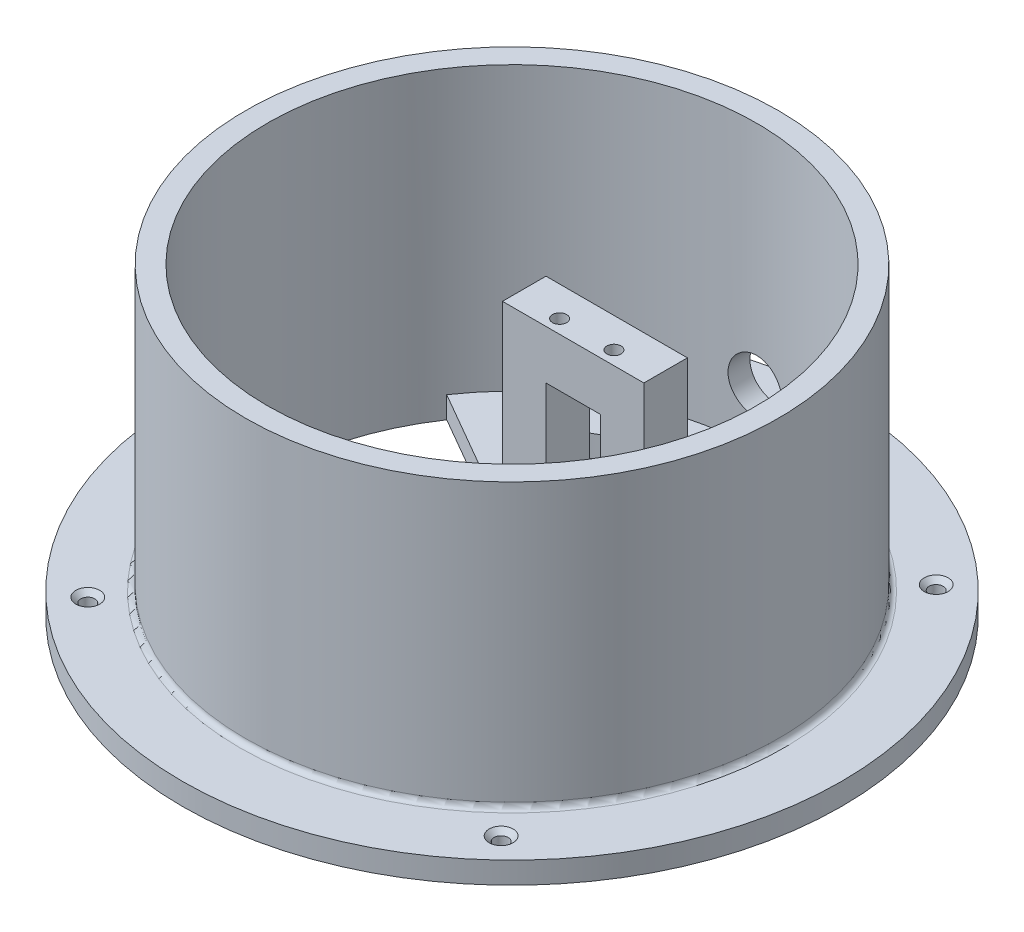
SolidWorks part; units mm, degrees
ref_plane "Front Plane" through (0, 0, 0) normal (0, 0, 1) x (1, 0, 0)
ref_plane "Top Plane" through (0, 0, 0) normal (0, 1, 0) x (1, 0, 0)
ref_plane "Right Plane" through (0, 0, 0) normal (1, 0, 0) x (0, 0, -1)
sketch "Sketch3" plane through (0, 0, 0) normal (0, 1, 0) x (1, 0, 0)
  circle A0 centre (0, 0) radius 60.625
  circle A1 centre (0, 0) radius 45
  dimension "D1" = 121.25
  dimension "D2" = 90
extrude "Boss-Extrude1" add sketch "Sketch3" along normal blind 4
sketch "Sketch5" plane through (0, 4, 0) normal (0, 1, 0) x (1, 0, 0)
  circle A0 centre (0, 0) radius 45 construction
  circle A1 centre (0, 0) radius 45
  circle A2 centre (0, 0) radius 49
  dimension "D1" = 4
extrude "Boss-Extrude2" add sketch "Sketch5" along normal blind 52
sketch "Sketch6" plane through (0, 0, 0) normal (1, 0, 0) x (0, 0, -1)
  line L0 (-46.75, 38) -> (-31.75, 38)
  line L1 (-31.75, 38) -> (-31.75, 30)
  line L3 (-46.75, 30) -> (-46.75, 38)
  line L4 (-45, 57.2969) -> (-45, 0)
  line L5 (-60.625, 0) -> (60.625, 0) construction
  line L6 (-31.75, 30) -> (-45, 16.75)
  line L7 (-45, 0) -> (45, 0) construction
  line L8 (11.25, 38) -> (19.25, 38)
  line L9 (11.25, 38) -> (11.25, 0)
  line L10 (11.25, 0) -> (19.25, 0)
  line L11 (19.25, 38) -> (19.25, 0)
  line L12 (49, 56) -> (-49, 56) construction
  line L13 (45, 56) -> (-45, 56) construction
  line L14 (-45, 16.75) -> (-46.75, 15)
  line L15 (-46.75, 30) -> (-46.75, 15)
  point P18 (-31.75, 34)
  dimension "D1" = 8
  dimension "D2" = 18
  dimension "D3" = 11.25
  dimension "D4" = 43
  dimension "D5" = 15
  dimension "D6" = 8
  dimension "D7" = 45
  dimension "D8" = 18
extrude "Boss-Extrude3" add sketch "Sketch6" along normal mid plane 26 contours L6 L14 L15 L3 L0 L1 | L9 L8 L11 L10
sketch "Sketch7" plane through (0, 0, -11.25) normal (0, 0, 1) x (1, 0, 0)
  line L0 (13, 38) -> (-13, 38) construction
  line L1 (-5, 5) -> (5, 5)
  line L2 (-5, 5) -> (-5, 29)
  line L3 (-5, 29) -> (5, 29)
  line L4 (5, 5) -> (5, 29)
  line L5 (-5, 5) -> (5, 29) construction
  line L6 (-5, 29) -> (5, 5) construction
  line L7 (13, 0) -> (-13, 0) construction
  point P0 (0, 17)
  dimension "D1" = 9
  dimension "D2" = 10
  dimension "D3" = 5
extrude "Cut-Extrude1" cut sketch "Sketch7" against normal blind 26
sketch "Sketch8" plane through (0, 0, -11.25) normal (0, 0, 1) x (1, 0, 0)
  circle A0 centre (0, 14) radius 5
  dimension "D1" = 10
  dimension "D2" = 14
extrude "Cut-Extrude2" cut sketch "Sketch8" against normal blind 55
sketch "Sketch9" plane through (0, 38, 0) normal (0, 1, 0) x (1, 0, 0)
  line L0 (5, 13.75) -> (-5, 13.75) construction
  line L1 (5, -34.25) -> (-5, -34.25) construction
  line L2 (13, -31.75) -> (-13, -31.75) construction
  circle A0 centre (-5, 13.75) radius 1.3
  circle A1 centre (5, 13.75) radius 1.3
  circle A2 centre (5, -34.25) radius 1.3
  circle A3 centre (-5, -34.25) radius 1.3
  dimension "D1" = 2.6
  dimension "D2" = 5
  dimension "D3" = 10
  dimension "D4" = 10
  dimension "D5" = 2.5
  dimension "D6" = 48
extrude "Cut-Extrude5" cut sketch "Sketch9" against normal blind 7.2 contours A1 | A2 | A3 | A0
sketch "Sketch10" plane through (0, 0, 0) normal (0, -1, 0) x (1, 0, 0)
  line L0 (13, -11.25) -> (-13, -11.25) construction
  line L1 (13, -11.25) -> (-13, -11.25)
  line L2 (0, 10.5988) -> (0, -40.7132) construction
  line L3 (-13, -11.25) -> (-37.2484, -25.2498)
  line L4 (13, -11.25) -> (37.2484, -25.2498)
  line L5 (19.5167, -24.25) -> (24.9065, -27.3618)
  line L7 (-19.5167, -24.25) -> (-24.9065, -27.3618)
  line L8 (-19.5167, -24.25) -> (19.5167, -24.25)
  line L9 (10.8564, -19.25) -> (24.9065, -27.3618) construction
  line L10 (10.8564, -19.25) -> (-10.8564, -19.25) construction
  line L11 (-10.8564, -19.25) -> (-24.9065, -27.3618) construction
  circle A0 centre (0, 0) radius 45 construction
  circle A1 centre (0, 0) radius 45
  arc A2 (-37.2484, -25.2498) -> (37.2484, -25.2498) centre (0, 0) ccw
  arc A3 (-24.9065, -27.3618) -> (24.9065, -27.3618) centre (0, 0) ccw
  point P16 (0, 0)
  point P18 (21.3282, -24.25)
  point P19 (-21.3589, -24.25)
  circle M13 centre (0, 0) radius 45
  dimension "D1" = 60
  dimension "D3" = 39.0333
  dimension "D2" = 8
extrude "Boss-Extrude5" add sketch "Sketch10" against normal blind 4 contours L4 L1 L3 A3 L7 L8 L5 M13
sketch "Sketch12" plane through (0, 4, 0) normal (0, 1, 0) x (1, 0, 0)
  line L1 (-38, 40) -> (38, 40) construction
  line L2 (-38, 40) -> (-38, -40) construction
  line L3 (-38, -40) -> (38, -40) construction
  line L4 (38, 40) -> (38, -40) construction
  line L5 (-38, 40) -> (38, -40) construction
  line L6 (-38, -40) -> (38, 40) construction
  point P0 (0, 0)
  point P1 (38, -40)
  point P2 (-38, 40)
  point P3 (-38, -40)
  point P4 (38, 40)
  dimension "D1" = 80
  dimension "D2" = 76
hole_wizard "CSK for ST2.2 Cross recessed CTSK head tapping screws1" positions "Sketch12" profile "Sketch13" countersink size "ST2.2" standard "GB" end condition through all
sketch "Sketch13" plane through (0, 4, 0) normal (1, 0, 0) x (0, 0, 1)
  line L0 (0, 0) -> (0, 4)
  line L1 (0, 4) -> (1.3, 4)
  line L2 (1.3, 4) -> (1.3, 0.9)
  line L3 (1.3, 0.9) -> (2.2, 0)
  line L5 (2.2, 0) -> (0, 0)
  line L6 (-1.3, 0.9) -> (-2.2, 0) construction
  line L11 (0, -6.35) -> (0, 107.95) construction
  dimension "Thru Hole Dia." = 2.6
  dimension "Thru Hole Depth" = 4
  dimension "Near C'Sink Dia." = 4.4
  dimension "Near C'Sink Angle" = 90
fillet "Fillet1" radius 1 1 edges at (0, 4, 49)
